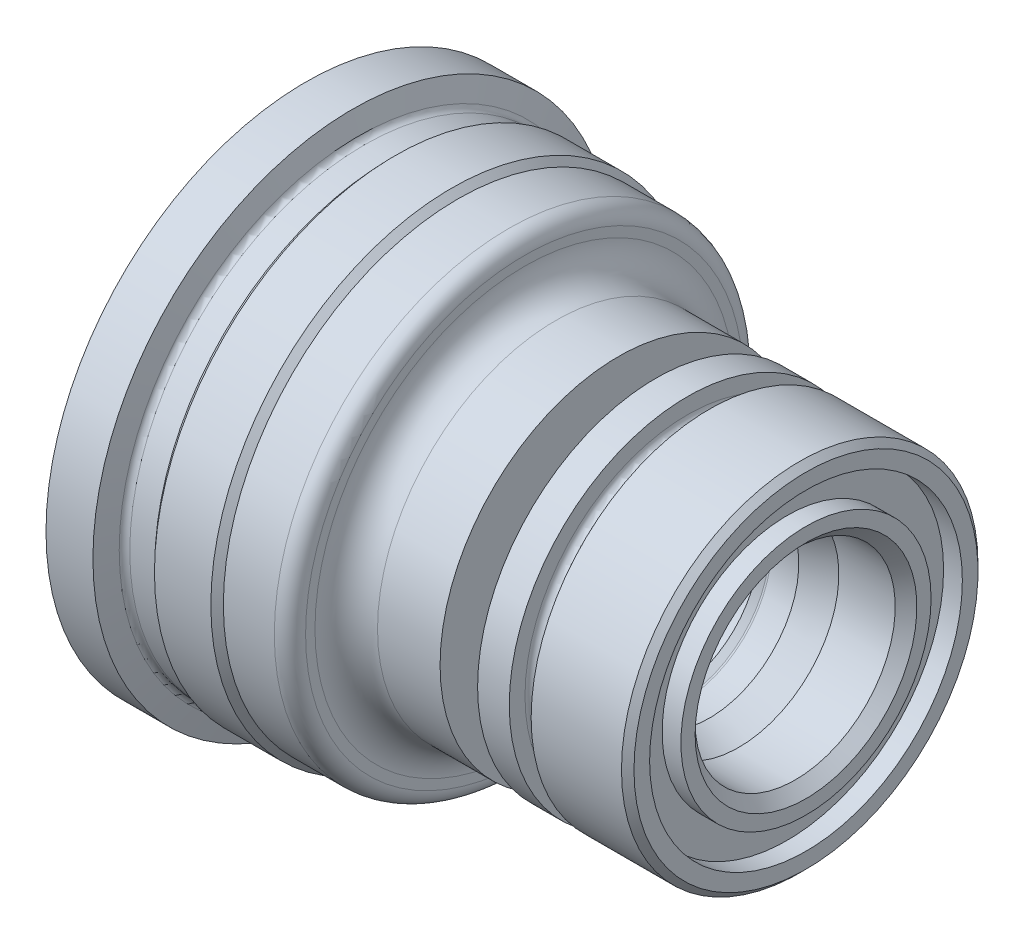
SolidWorks part; units mm, degrees
ref_plane "Plane1" through (0, 0, 0) normal (0, 0, 1) x (1, 0, 0)
ref_plane "Plane2" through (0, 0, 0) normal (0, 1, 0) x (1, 0, 0)
ref_plane "Plane3" through (0, 0, 0) normal (1, 0, 0) x (0, 0, -1)
sketch "Sketch1" plane through (0, 0, 0) normal (0, 0, 1) x (1, 0, 0)
  line L0 (78.6624, 22.5148) -> (78.6624, 36.195)
  line L1 (73.1299, 36.195) -> (59.055, 36.195)
  line L2 (21.5124, 42.545) -> (21.5124, 44.45)
  line L3 (40.5624, 36.195) -> (27.8624, 36.195)
  line L4 (54.61, 36.195) -> (48.1824, 36.195)
  line L5 (18.3374, 47.625) -> (7.9911, 47.625)
  line L6 (7.9911, 47.625) -> (6.7211, 48.895)
  line L7 (6.7211, 48.895) -> (-4.7303, 48.895)
  line L8 (-4.7303, 48.895) -> (-5.9287, 47.625)
  line L9 (-5.9287, 47.625) -> (-11.0087, 47.625)
  line L10 (-13.4126, 52.705) -> (-12.2303, 48.5476)
  line L12 (-13.4126, 52.705) -> (-22.9376, 52.705)
  line L13 (-22.9376, 52.705) -> (-22.9376, 17.145)
  line L14 (37.3755, 17.145) -> (51.9985, 17.145)
  line L16 (37.3755, 17.145) -> (37.3755, 19.05)
  line L17 (36.1055, 20.32) -> (29.7555, 20.32)
  line L18 (-22.9376, 17.145) -> (28.4855, 17.145)
  line L19 (51.9985, 17.145) -> (53.2045, 18.0495)
  line L20 (78.6624, 22.5148) -> (76.4675, 20.32)
  line L21 (53.5093, 18.1511) -> (59.055, 18.1511)
  line L22 (59.055, 18.1511) -> (65.014, 20.32)
  line L23 (65.014, 20.32) -> (76.4675, 20.32)
  line L24 (74.93, 0) -> (85.9686, 0) construction
  line L26 (73.1299, 36.195) -> (78.6624, 36.195)
  line L27 (59.055, 36.195) -> (59.055, 33.0008)
  line L28 (57.785, 31.7308) -> (55.88, 31.7308)
  line L29 (54.61, 36.195) -> (54.61, 33.0008)
  line L30 (28.4855, 17.145) -> (28.4855, 19.05)
  line L31 (40.5624, 36.195) -> (40.5624, 22.606)
  line L32 (41.8324, 21.336) -> (46.9124, 21.336)
  line L33 (48.1824, 36.195) -> (48.1824, 22.606)
  line L34 (50, 0) -> (-50, 0) construction
  arc A0 (-11.0087, 47.625) -> (-12.2303, 48.5476) centre (-11.0087, 48.895) cw
  arc A1 (27.8624, 36.195) -> (21.5124, 42.545) centre (27.8624, 42.545) cw
  arc A3 (21.5124, 44.45) -> (18.3374, 47.625) centre (18.3374, 44.45) ccw
  arc A4 (28.4855, 19.05) -> (29.7555, 20.32) centre (29.7555, 19.05) cw
  arc A6 (53.5093, 18.1511) -> (53.2045, 18.0495) centre (53.5093, 17.6431) ccw
  arc A7 (36.1055, 20.32) -> (37.3755, 19.05) centre (36.1055, 19.05) cw
  arc A8 (41.8324, 21.336) -> (40.5624, 22.606) centre (41.8324, 22.606) cw
  arc A10 (48.1824, 22.606) -> (46.9124, 21.336) centre (46.9124, 22.606) cw
  arc A11 (54.61, 33.0008) -> (55.88, 31.7308) centre (55.88, 33.0008) ccw
  arc A12 (57.785, 31.7308) -> (59.055, 33.0008) centre (57.785, 33.0008) ccw
  point P52 (28.4855, 20.32)
  point P55 (37.3755, 20.32)
  dimension "D7" = 1.27
  dimension "D8" = 3.175
  dimension "D12" = 5.08
  dimension "D15" = 1.27
  dimension "D5" = 9.525
  dimension "D6" = 6.35
  dimension "D1" = 17.145
  dimension "D2" = 101.6
  dimension "D3" = 19.05
  dimension "D4" = 31.75
  dimension "D9" = 44.45
  dimension "D10" = 30.48
  dimension "D11" = 35.56
  dimension "D13" = 8.89
  dimension "D14" = 3.175
  dimension "D16" = 14.859
  dimension "D17" = 22.9376
  dimension "D18" = 1.0061
  dimension "D19" = 3.175
  dimension "D20" = 3.104
  dimension "D21" = 20
  dimension "D22" = 45
  dimension "D23" = 4.445
  dimension "D24" = 19.6074
  dimension "D25" = 7.62
  dimension "D26" = 30.48
  dimension "D27" = 14.7913
  dimension "D28" = 11.4514
  dimension "D29" = 17.0089
  dimension "D31" = 13.5213
revolve "Base-Revolve" add sketch "Sketch1" angle 360 about L24
chamfer "Chamfer1" distance 1.27 angle 45
sketch "Sketch2" plane through (78.6624, 0, 0) normal (1, 0, 0) x (0, 0, -1)
  circle A0 centre (0, 0) radius 31.75
  circle A1 centre (0, 0) radius 25.4
  dimension "D2" = 63.5
  dimension "D1" = 6.35
extrude "Cut-Extrude1" cut sketch "Sketch2" against normal blind 3.81
sketch "Stock Sketch" plane through (0, 0, 0) normal (0, 0, 1) x (1, 0, 0)
  line L0 (-28.0176, 0) -> (-28.0176, 57.15)
  line L1 (-21.6676, 63.5) -> (19.1519, 63.5)
  line L2 (22.7979, 62.3489) -> (37.6241, 51.9511)
  line L3 (41.2701, 50.8) -> (72.9474, 50.8)
  line L4 (82.4724, 41.275) -> (82.4724, 0)
  line L5 (82.4724, 0) -> (-28.0176, 0)
  line L6 (77.3924, 0) -> (78.6624, 0) construction
  line L7 (78.6624, -34.925) -> (78.6624, 34.925) construction
  line L9 (-22.9376, 52.705) -> (-22.9376, -52.705) construction
  arc A0 (22.7979, 62.3489) -> (19.1519, 63.5) centre (19.1519, 57.15) ccw
  arc A1 (82.4724, 41.275) -> (72.9474, 50.8) centre (72.9474, 41.275) ccw
  arc A2 (37.6241, 51.9511) -> (41.2701, 50.8) centre (41.2701, 57.15) ccw
  arc A3 (-21.6676, 63.5) -> (-28.0176, 57.15) centre (-21.6676, 57.15) ccw
  dimension "D1" = 6.35
  dimension "D2" = 6.35
  dimension "D7" = 5.08
  dimension "D6" = 9.525
  dimension "D3" = 63.5
  dimension "D4" = 50.8
  dimension "D5" = 3.81
sketch "Sketch4" plane through (-22.9376, 0, 0) normal (-1, 0, 0) x (0, 0, 1)
  circle A1 centre (0, 0) radius 36.83
  circle A2 centre (0, 0) radius 27.305
  circle A3 centre (0, 0) radius 27.305
  dimension "D1" = 25.4
  dimension "D2" = 9.525
extrude "Cut-Extrude2" cut sketch "Sketch4" against normal blind 6.35
chamfer "Chamfer2" distance 1.27 angle 45
